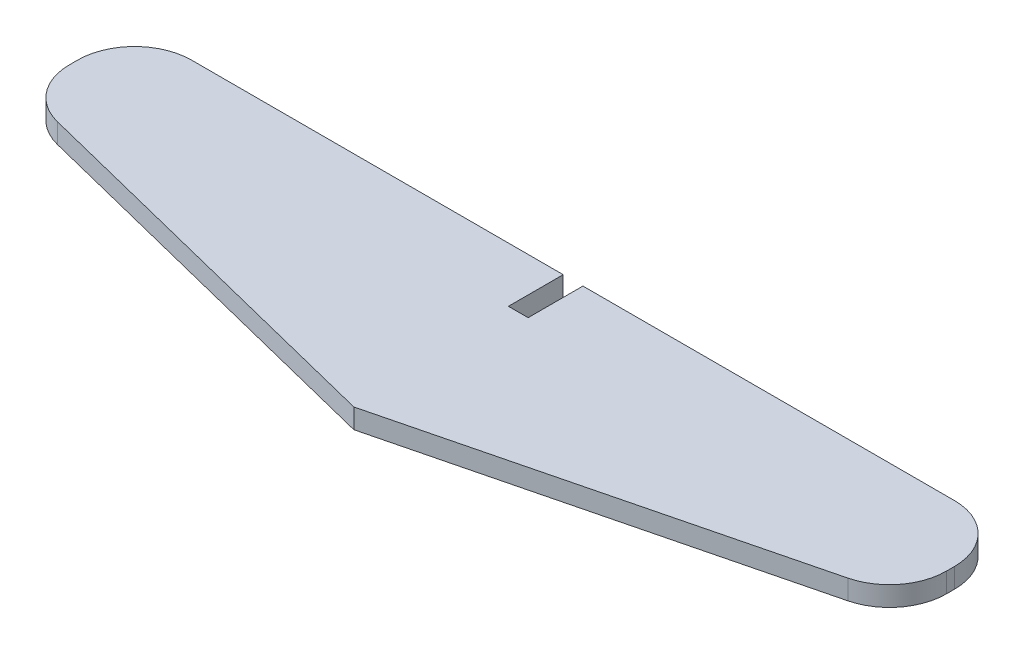
SolidWorks part; units mm, degrees
material "Balsa"
ref_plane "Front" through (0, 0, 0) normal (0, 0, 1) x (1, 0, 0)
ref_plane "Top" through (0, 0, 0) normal (0, 1, 0) x (1, 0, 0)
ref_plane "Right" through (0, 0, 0) normal (1, 0, 0) x (0, 0, -1)
sketch "Sketch1" plane through (0, 0, 0) normal (0, 1, 0) x (1, 0, 0)
  line L1 (110.2198, 25) -> (110.2198, 50)
  line L2 (110.2198, 50) -> (12.4698, 50)
  line L3 (-89.7802, 50) -> (-89.7802, 25)
  line L4 (10.2198, 0) -> (-89.7802, 25)
  line L5 (10.2198, 0) -> (110.2198, 25)
  line L6 (7.9698, 50) -> (7.9698, 37.5)
  line L7 (7.9698, 37.5) -> (12.4698, 37.5)
  line L8 (12.4698, 37.5) -> (12.4698, 50)
  line L9 (7.9698, 50) -> (-89.7802, 50)
  point P2 (0, 0)
  point P10 (10.2198, 37.5)
  dimension "D1" = 200
  dimension "D2" = 50
  dimension "D3" = 25
  dimension "D4" = 25
  dimension "D5" = 4.5
  dimension "D6" = 12.5
extrude "Boss-Extrude1" add sketch "Sketch1" along normal blind 4.5
fillet "Fillet1" radius 13 4 edges at (-89.7802, 2.25, -25) (-89.7802, 2.25, -50) (110.2198, 2.25, -50) (110.2198, 2.25, -25)
